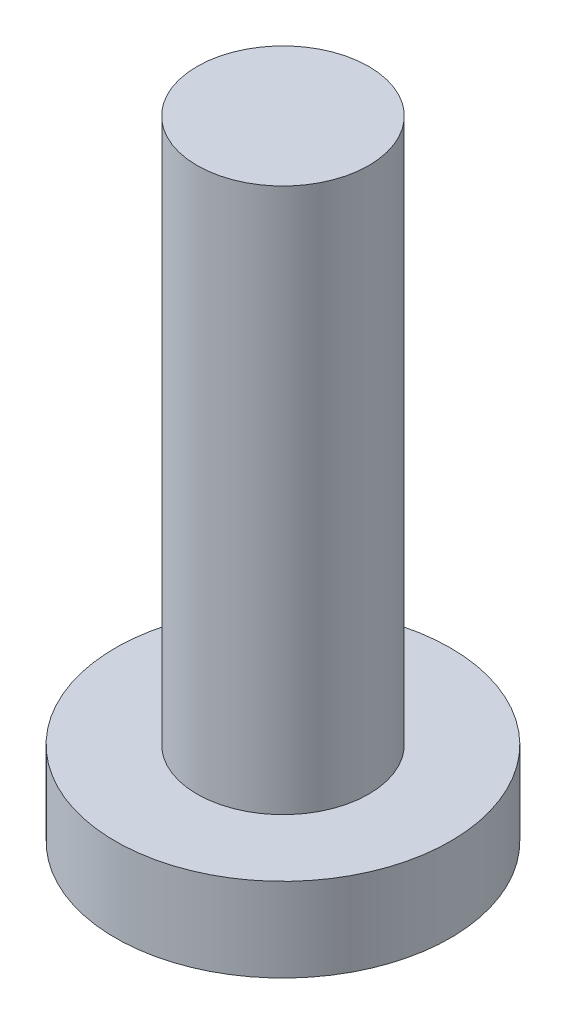
SolidWorks part; units mm, degrees
ref_plane "Front Plane" through (0, 0, 0) normal (0, 0, 1) x (1, 0, 0)
ref_plane "Top Plane" through (0, 0, 0) normal (0, 1, 0) x (1, 0, 0)
ref_plane "Right Plane" through (0, 0, 0) normal (1, 0, 0) x (0, 0, -1)
sketch "Sketch2" plane through (0, 0, 0) normal (0, 1, 0) x (1, 0, 0)
  circle A0 centre (0, 0) radius 1.025
  dimension "D1" = 2.05
extrude "Boss-Extrude1" add sketch "Sketch2" along normal blind 6.5
sketch "Sketch3" plane through (0, 0, 0) normal (0, -1, 0) x (1, 0, 0)
  circle A0 centre (0, 0) radius 2
extrude "Boss-Extrude2" add sketch "Sketch3" along normal blind 1
